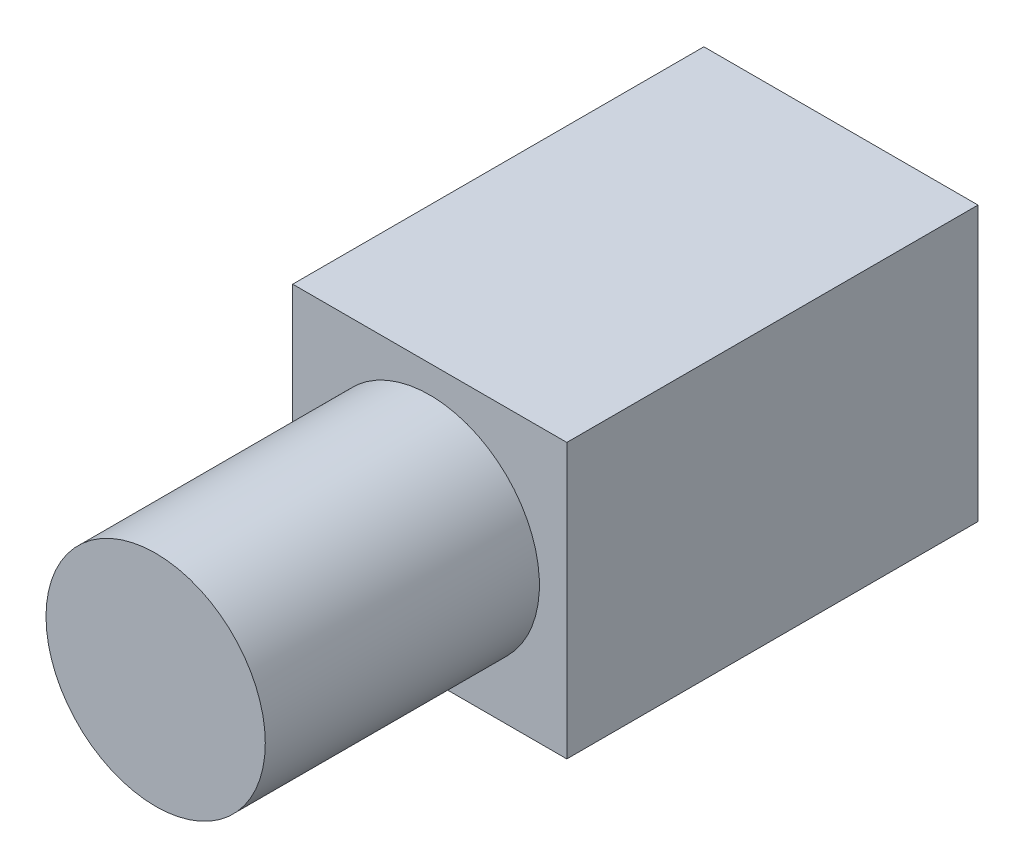
SolidWorks part; units mm, degrees
ref_plane "正面" through (0, 0, 0) normal (0, 0, 1) x (1, 0, 0)
ref_plane "平面" through (0, 0, 0) normal (0, 1, 0) x (1, 0, 0)
ref_plane "右側面" through (0, 0, 0) normal (1, 0, 0) x (0, 0, -1)
sketch "ｽｹｯﾁ3" plane through (0, 0, 0) normal (0, 0, 1) x (1, 0, 0)
  line L1 (0, 0) -> (10, 0)
  line L2 (0, 0) -> (0, 10)
  line L3 (0, 10) -> (10, 10)
  line L4 (10, 0) -> (10, 10)
  dimension "D1" = 10
  dimension "D2" = 10
extrude "ﾎﾞｽ - 押し出し3" add sketch "ｽｹｯﾁ3" along normal blind 15
sketch "ｽｹｯﾁ4" plane through (0, 0, 15) normal (0, 0, 1) x (1, 0, 0)
  circle A0 centre (5, 5) radius 4
  dimension "D1" = 8
extrude "ﾎﾞｽ - 押し出し4" add sketch "ｽｹｯﾁ4" along normal blind 10
